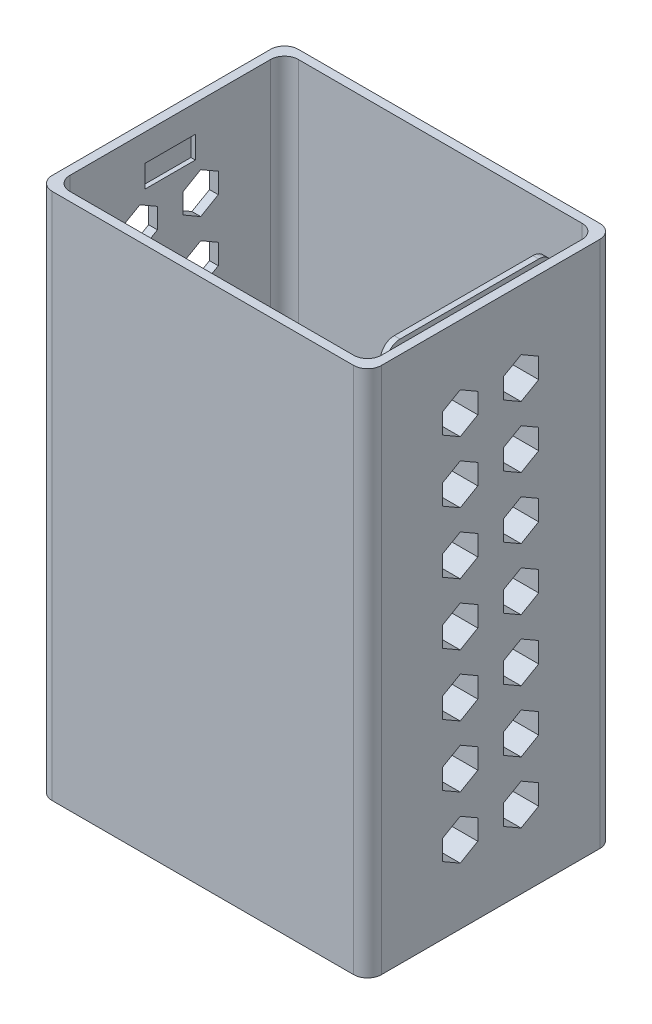
SolidWorks part; units mm, degrees
ref_plane "Front Plane" through (0, 0, 0) normal (0, 0, 1) x (1, 0, 0)
ref_plane "Top Plane" through (0, 0, 0) normal (0, 1, 0) x (1, 0, 0)
ref_plane "Right Plane" through (0, 0, 0) normal (1, 0, 0) x (0, 0, -1)
sketch "Sketch1" plane through (0, 0, 0) normal (0, 1, 0) x (1, 0, 0)
  line L0 (-6.35, 6.35) -> (-6.35, -171.3484)
  line L1 (0, 0) -> (224.9932, 0)
  line L2 (0, 0) -> (0, -164.9984)
  line L3 (0, -164.9984) -> (224.9932, -164.9984)
  line L4 (224.9932, 0) -> (224.9932, -164.9984)
  line L5 (-6.35, -171.3484) -> (231.3432, -171.3484)
  line L6 (231.3432, 6.35) -> (231.3432, -171.3484)
  line L7 (-6.35, 6.35) -> (231.3432, 6.35)
  dimension "D1" = 224.9932
  dimension "D2" = 164.9984
  dimension "D3" = 6.35
extrude "Boss-Extrude1" add sketch "Sketch1" along normal blind 374.65
sketch "Sketch4" plane through (224.9932, 0, 0) normal (-1, 0, 0) x (0, 0, 1)
  line L0 (164.9984, 0) -> (0, 0) construction
  line L1 (28.7274, 0) -> (136.1694, 0)
  line L2 (28.7274, 0) -> (28.7274, 374.65)
  line L3 (28.7274, 374.65) -> (136.1694, 374.65)
  line L4 (136.1694, 0) -> (136.1694, 374.65)
  line L5 (164.9984, 374.65) -> (0, 374.65) construction
  line L8 (164.9984, 374.65) -> (164.9984, 0) construction
  dimension "D1" = 107.442
  dimension "D2" = 28.829
extrude "Boss-Extrude2" add sketch "Sketch4" along normal blind 9.017
sketch "Sketch5" plane through (215.9762, 0, 0) normal (-1, 0, 0) x (0, 0, 1)
  line L0 (136.1694, 374.65) -> (28.7274, 374.65) construction
  line L5 (142.5194, 0) -> (22.3774, 0)
  line L6 (142.5194, 0) -> (142.5194, 374.65)
  line L7 (142.5194, 374.65) -> (22.3774, 374.65)
  line L8 (22.3774, 0) -> (22.3774, 374.65)
  line L9 (28.7274, 0) -> (136.1694, 0) construction
  line L11 (164.9984, 374.65) -> (164.9984, 0) construction
  line L12 (136.1694, 0) -> (136.1694, 374.65) construction
  line L13 (28.7274, 374.65) -> (28.7274, 0) construction
  dimension "D1" = 6.35
  dimension "D2" = 6.35
extrude "Boss-Extrude3" add sketch "Sketch5" along normal blind 4.191
sketch "Sketch7" plane through (0, 374.65, 0) normal (0, 1, 0) x (1, 0, 0)
  line L1 (215.9762, -136.1694) -> (224.9932, -136.1694)
  line L2 (215.9762, -136.1694) -> (215.9762, -28.7274)
  line L3 (215.9762, -28.7274) -> (224.9932, -28.7274)
  line L4 (224.9932, -136.1694) -> (224.9932, -28.7274)
extrude "Cut-Extrude1" cut sketch "Sketch7" against normal blind 21.59
sketch "Sketch10" plane through (0, 374.65, 0) normal (0, 1, 0) x (1, 0, 0)
  line L1 (211.7852, -142.5194) -> (215.9762, -142.5194)
  line L2 (211.7852, -142.5194) -> (211.7852, -22.3774)
  line L3 (211.7852, -22.3774) -> (215.9762, -22.3774)
  line L4 (215.9762, -142.5194) -> (215.9762, -22.3774)
extrude "Cut-Extrude2" cut sketch "Sketch10" against normal blind 5.588
fillet "Fillet1" radius 10 1 edges at (231.3432, 187.325, 171.3484)
fillet "Fillet2" radius 10 1 edges at (224.9932, 187.325, 164.9984)
fillet "Fillet3" radius 10 2 edges at (231.3432, 187.325, -6.35) (224.9932, 187.325, 0)
fillet "Fillet4" radius 10 2 edges at (-6.35, 187.325, 171.3484) (0, 187.325, 164.9984)
fillet "Fillet5" radius 10 2 edges at (0, 187.325, 0) (-6.35, 187.325, -6.35)
fillet "Fillet6" radius 10 2 edges at (220.4847, 353.06, 136.1694) (220.4847, 353.06, 28.7274)
fillet "Fillet7" radius 10 2 edges at (213.8807, 369.062, 22.3774) (213.8807, 369.062, 142.5194)
sketch "Sketch11" plane through (211.7852, 0, 0) normal (-1, 0, 0) x (0, 0, 1)
  line L0 (22.3774, 0) -> (142.5194, 0) construction
  line L1 (57.0484, 0) -> (107.8484, 0)
  line L2 (57.0484, 0) -> (57.0484, 15.24)
  line L3 (57.0484, 15.24) -> (107.8484, 15.24)
  line L4 (107.8484, 0) -> (107.8484, 15.24)
  line L5 (142.5194, 0) -> (142.5194, 359.062) construction
  dimension "D1" = 15.24
  dimension "D2" = 50.8
  dimension "D3" = 34.671
extrude "Boss-Extrude4" add sketch "Sketch11" along normal blind 19.9898
fillet "Fillet10" radius 10 2 edges at (191.7954, 7.62, 107.8484) (191.7954, 7.62, 57.0484)
fillet "Fillet11" radius 10 5 edges at (206.7903, 15.24, 107.8484) (194.7243, 15.24, 104.9195) (206.7903, 15.24, 57.0484) (194.7243, 15.24, 59.9773) (191.7954, 15.24, 82.4484)
sketch "Sketch12" plane through (0, 0, 0) normal (0, -1, 0) x (1, 0, 0)
  line L0 (231.3432, 161.3484) -> (231.3432, 3.65) construction
  line L1 (221.3432, -6.35) -> (3.65, -6.35) construction
  line L2 (-6.35, 3.65) -> (-6.35, 161.3484) construction
  line L3 (3.65, 171.3484) -> (221.3432, 171.3484) construction
  line L4 (231.3432, 161.3484) -> (231.3432, 3.65)
  line L5 (221.3432, -6.35) -> (3.65, -6.35)
  line L6 (-6.35, 3.65) -> (-6.35, 161.3484)
  line L7 (3.65, 171.3484) -> (221.3432, 171.3484)
  arc A0 (231.3432, 161.3484) -> (221.3432, 171.3484) centre (221.3432, 161.3484) ccw construction
  arc A1 (221.3432, -6.35) -> (231.3432, 3.65) centre (221.3432, 3.65) ccw construction
  arc A2 (-6.35, 3.65) -> (3.65, -6.35) centre (3.65, 3.65) ccw construction
  arc A3 (3.65, 171.3484) -> (-6.35, 161.3484) centre (3.65, 161.3484) ccw construction
  arc A4 (231.3432, 161.3484) -> (221.3432, 171.3484) centre (221.3432, 161.3484) ccw
  arc A5 (221.3432, -6.35) -> (231.3432, 3.65) centre (221.3432, 3.65) ccw
  arc A6 (-6.35, 3.65) -> (3.65, -6.35) centre (3.65, 3.65) ccw
  arc A7 (3.65, 171.3484) -> (-6.35, 161.3484) centre (3.65, 161.3484) ccw
extrude "Boss-Extrude5" add sketch "Sketch12" along normal blind 6.35
fillet "Fillet13" radius 10 9 edges at (224.9932, 0, 19.3637) (222.0643, 0, 2.9289) (112.4966, 0, 0) (2.9289, 0, 2.9289) (224.9932, 0, 145.5839) (222.0643, 0, 162.0695) (112.4966, 0, 164.9984) (2.9289, 0, 162.0695) (0, 0, 82.4992)
sketch "Sketch13" plane through (0, 0, 0) normal (1, 0, 0) x (0, 0, -1)
  line L0 (-10, 374.65) -> (-154.9984, 374.65) construction
  line L1 (-100.7542, 355.0412) -> (-64.356, 355.0412)
  line L2 (-100.7542, 355.0412) -> (-100.7542, 338.9122)
  line L3 (-100.7542, 338.9122) -> (-64.356, 338.9122)
  line L4 (-64.356, 355.0412) -> (-64.356, 338.9122)
  line L5 (-10, 10) -> (-10, 374.65) construction
  dimension "D1" = 19.6088
  dimension "D2" = 16.129
  dimension "D3" = 36.3982
  dimension "D4" = 54.356
extrude "Cut-Extrude4" cut sketch "Sketch13" against normal blind 3.175
sketch "Sketch15" plane through (0, -6.35, 0) normal (0, -1, 0) x (1, 0, 0)
  line L0 (177.8, 131.1399) -> (184.15, 134.8061)
  line L1 (196.85, 131.1399) -> (203.2, 134.8061)
  line L2 (203.2, 134.8061) -> (203.2, 142.1384)
  line L3 (203.2, 142.1384) -> (196.85, 145.8046)
  line L4 (196.85, 145.8046) -> (190.5, 142.1384)
  line L5 (190.5, 142.1384) -> (190.5, 134.8061)
  line L6 (190.5, 134.8061) -> (196.85, 131.1399)
  line L7 (171.45, 134.8061) -> (177.8, 131.1399)
  line L8 (171.45, 142.1384) -> (171.45, 134.8061)
  line L9 (177.8, 145.8046) -> (171.45, 142.1384)
  line L10 (184.15, 142.1384) -> (177.8, 145.8046)
  line L11 (184.15, 134.8061) -> (184.15, 142.1384)
  line L12 (158.75, 131.1399) -> (165.1, 134.8061)
  line L13 (152.4, 134.8061) -> (158.75, 131.1399)
  line L14 (152.4, 142.1384) -> (152.4, 134.8061)
  line L15 (158.75, 145.8046) -> (152.4, 142.1384)
  line L16 (165.1, 142.1384) -> (158.75, 145.8046)
  line L17 (165.1, 134.8061) -> (165.1, 142.1384)
  line L18 (139.7, 131.1399) -> (146.05, 134.8061)
  line L19 (133.35, 134.8061) -> (139.7, 131.1399)
  line L20 (133.35, 142.1384) -> (133.35, 134.8061)
  line L21 (139.7, 145.8046) -> (133.35, 142.1384)
  line L22 (146.05, 142.1384) -> (139.7, 145.8046)
  line L23 (146.05, 134.8061) -> (146.05, 142.1384)
  line L24 (120.65, 131.1399) -> (127, 134.8061)
  line L25 (114.3, 134.8061) -> (120.65, 131.1399)
  line L26 (114.3, 142.1384) -> (114.3, 134.8061)
  line L27 (120.65, 145.8046) -> (114.3, 142.1384)
  line L28 (127, 142.1384) -> (120.65, 145.8046)
  line L29 (127, 134.8061) -> (127, 142.1384)
  line L30 (-6.35, 161.3484) -> (-6.35, 3.65) construction
  line L31 (231.3432, 3.65) -> (231.3432, 161.3484) construction
  line L32 (3.65, -6.35) -> (221.3432, -6.35) construction
  line L38 (101.6, 131.1399) -> (107.95, 134.8061)
  line L39 (95.25, 134.8061) -> (101.6, 131.1399)
  line L40 (95.25, 142.1384) -> (95.25, 134.8061)
  line L41 (101.6, 145.8046) -> (95.25, 142.1384)
  line L42 (107.95, 142.1384) -> (101.6, 145.8046)
  line L43 (107.95, 134.8061) -> (107.95, 142.1384)
  line L44 (82.55, 131.1399) -> (88.9, 134.8061)
  line L45 (76.2, 134.8061) -> (82.55, 131.1399)
  line L46 (76.2, 142.1384) -> (76.2, 134.8061)
  line L47 (82.55, 145.8046) -> (76.2, 142.1384)
  line L48 (88.9, 142.1384) -> (82.55, 145.8046)
  line L49 (88.9, 134.8061) -> (88.9, 142.1384)
  line L50 (63.5, 131.1399) -> (69.85, 134.8061)
  line L51 (57.15, 134.8061) -> (63.5, 131.1399)
  line L52 (57.15, 142.1384) -> (57.15, 134.8061)
  line L53 (63.5, 145.8046) -> (57.15, 142.1384)
  line L54 (69.85, 142.1384) -> (63.5, 145.8046)
  line L55 (69.85, 134.8061) -> (69.85, 142.1384)
  line L56 (44.45, 131.1399) -> (50.8, 134.8061)
  line L57 (38.1, 134.8061) -> (44.45, 131.1399)
  line L58 (38.1, 142.1384) -> (38.1, 134.8061)
  line L59 (44.45, 145.8046) -> (38.1, 142.1384)
  line L60 (50.8, 142.1384) -> (44.45, 145.8046)
  line L61 (50.8, 134.8061) -> (50.8, 142.1384)
  line L62 (25.4, 131.1399) -> (31.75, 134.8061)
  line L63 (19.05, 134.8061) -> (25.4, 131.1399)
  line L64 (19.05, 142.1384) -> (19.05, 134.8061)
  line L65 (25.4, 145.8046) -> (19.05, 142.1384)
  line L66 (31.75, 142.1384) -> (25.4, 145.8046)
  line L67 (31.75, 134.8061) -> (31.75, 142.1384)
  line L74 (32.4716, 113.2256) -> (38.8216, 116.8918)
  line L75 (26.1216, 116.8918) -> (32.4716, 113.2256)
  line L76 (26.1216, 124.2241) -> (26.1216, 116.8918)
  line L77 (32.4716, 127.8903) -> (26.1216, 124.2241)
  line L78 (38.8216, 124.2241) -> (32.4716, 127.8903)
  line L79 (38.8216, 116.8918) -> (38.8216, 124.2241)
  line L80 (51.5216, 113.2256) -> (57.8716, 116.8918)
  line L81 (57.8716, 116.8918) -> (57.8716, 124.2241)
  line L82 (57.8716, 124.2241) -> (51.5216, 127.8903)
  line L83 (51.5216, 127.8903) -> (45.1716, 124.2241)
  line L84 (45.1716, 124.2241) -> (45.1716, 116.8918)
  line L85 (45.1716, 116.8918) -> (51.5216, 113.2256)
  line L86 (70.5716, 113.2256) -> (76.9216, 116.8918)
  line L87 (76.9216, 116.8918) -> (76.9216, 124.2241)
  line L88 (76.9216, 124.2241) -> (70.5716, 127.8903)
  line L89 (70.5716, 127.8903) -> (64.2216, 124.2241)
  line L90 (64.2216, 124.2241) -> (64.2216, 116.8918)
  line L91 (64.2216, 116.8918) -> (70.5716, 113.2256)
  line L92 (89.6216, 113.2256) -> (95.9716, 116.8918)
  line L93 (95.9716, 116.8918) -> (95.9716, 124.2241)
  line L94 (95.9716, 124.2241) -> (89.6216, 127.8903)
  line L95 (89.6216, 127.8903) -> (83.2716, 124.2241)
  line L96 (83.2716, 124.2241) -> (83.2716, 116.8918)
  line L97 (83.2716, 116.8918) -> (89.6216, 113.2256)
  line L98 (108.6716, 113.2256) -> (115.0216, 116.8918)
  line L99 (115.0216, 116.8918) -> (115.0216, 124.2241)
  line L100 (115.0216, 124.2241) -> (108.6716, 127.8903)
  line L101 (108.6716, 127.8903) -> (102.3216, 124.2241)
  line L102 (102.3216, 124.2241) -> (102.3216, 116.8918)
  line L103 (102.3216, 116.8918) -> (108.6716, 113.2256)
  line L104 (127.7216, 113.2256) -> (134.0716, 116.8918)
  line L105 (134.0716, 116.8918) -> (134.0716, 124.2241)
  line L106 (134.0716, 124.2241) -> (127.7216, 127.8903)
  line L107 (127.7216, 127.8903) -> (121.3716, 124.2241)
  line L108 (121.3716, 124.2241) -> (121.3716, 116.8918)
  line L109 (121.3716, 116.8918) -> (127.7216, 113.2256)
  line L110 (146.7716, 113.2256) -> (153.1216, 116.8918)
  line L111 (153.1216, 116.8918) -> (153.1216, 124.2241)
  line L112 (153.1216, 124.2241) -> (146.7716, 127.8903)
  line L113 (146.7716, 127.8903) -> (140.4216, 124.2241)
  line L114 (140.4216, 124.2241) -> (140.4216, 116.8918)
  line L115 (140.4216, 116.8918) -> (146.7716, 113.2256)
  line L116 (165.8216, 113.2256) -> (172.1716, 116.8918)
  line L117 (172.1716, 116.8918) -> (172.1716, 124.2241)
  line L118 (172.1716, 124.2241) -> (165.8216, 127.8903)
  line L119 (165.8216, 127.8903) -> (159.4716, 124.2241)
  line L120 (159.4716, 124.2241) -> (159.4716, 116.8918)
  line L121 (159.4716, 116.8918) -> (165.8216, 113.2256)
  line L122 (184.8716, 113.2256) -> (191.2216, 116.8918)
  line L123 (191.2216, 116.8918) -> (191.2216, 124.2241)
  line L124 (191.2216, 124.2241) -> (184.8716, 127.8903)
  line L125 (184.8716, 127.8903) -> (178.5216, 124.2241)
  line L126 (178.5216, 124.2241) -> (178.5216, 116.8918)
  line L127 (178.5216, 116.8918) -> (184.8716, 113.2256)
  line L128 (25.4, 95.3113) -> (31.75, 98.9775)
  line L129 (31.75, 98.9775) -> (31.75, 106.3099)
  line L130 (31.75, 106.3099) -> (25.4, 109.976)
  line L131 (25.4, 109.976) -> (19.05, 106.3099)
  line L132 (19.05, 106.3099) -> (19.05, 98.9775)
  line L133 (19.05, 98.9775) -> (25.4, 95.3113)
  line L134 (44.45, 95.3113) -> (50.8, 98.9775)
  line L135 (50.8, 98.9775) -> (50.8, 106.3099)
  line L136 (50.8, 106.3099) -> (44.45, 109.976)
  line L137 (44.45, 109.976) -> (38.1, 106.3099)
  line L138 (38.1, 106.3099) -> (38.1, 98.9775)
  line L139 (38.1, 98.9775) -> (44.45, 95.3113)
  line L140 (63.5, 95.3113) -> (69.85, 98.9775)
  line L141 (69.85, 98.9775) -> (69.85, 106.3099)
  line L142 (69.85, 106.3099) -> (63.5, 109.976)
  line L143 (63.5, 109.976) -> (57.15, 106.3099)
  line L144 (57.15, 106.3099) -> (57.15, 98.9775)
  line L145 (57.15, 98.9775) -> (63.5, 95.3113)
  line L146 (82.55, 95.3113) -> (88.9, 98.9775)
  line L147 (88.9, 98.9775) -> (88.9, 106.3099)
  line L148 (88.9, 106.3099) -> (82.55, 109.976)
  line L149 (82.55, 109.976) -> (76.2, 106.3099)
  line L150 (76.2, 106.3099) -> (76.2, 98.9775)
  line L151 (76.2, 98.9775) -> (82.55, 95.3113)
  line L152 (101.6, 95.3113) -> (107.95, 98.9775)
  line L153 (107.95, 98.9775) -> (107.95, 106.3099)
  line L154 (107.95, 106.3099) -> (101.6, 109.976)
  line L155 (101.6, 109.976) -> (95.25, 106.3099)
  line L156 (95.25, 106.3099) -> (95.25, 98.9775)
  line L157 (95.25, 98.9775) -> (101.6, 95.3113)
  line L158 (120.65, 95.3113) -> (127, 98.9775)
  line L159 (127, 98.9775) -> (127, 106.3099)
  line L160 (127, 106.3099) -> (120.65, 109.976)
  line L161 (120.65, 109.976) -> (114.3, 106.3099)
  line L162 (114.3, 106.3099) -> (114.3, 98.9775)
  line L163 (114.3, 98.9775) -> (120.65, 95.3113)
  line L164 (139.7, 95.3113) -> (146.05, 98.9775)
  line L165 (146.05, 98.9775) -> (146.05, 106.3099)
  line L166 (146.05, 106.3099) -> (139.7, 109.976)
  line L167 (139.7, 109.976) -> (133.35, 106.3099)
  line L168 (133.35, 106.3099) -> (133.35, 98.9775)
  line L169 (133.35, 98.9775) -> (139.7, 95.3113)
  line L170 (158.75, 95.3113) -> (165.1, 98.9775)
  line L171 (165.1, 98.9775) -> (165.1, 106.3099)
  line L172 (165.1, 106.3099) -> (158.75, 109.976)
  line L173 (158.75, 109.976) -> (152.4, 106.3099)
  line L174 (152.4, 106.3099) -> (152.4, 98.9775)
  line L175 (152.4, 98.9775) -> (158.75, 95.3113)
  line L176 (177.8, 95.3113) -> (184.15, 98.9775)
  line L177 (184.15, 98.9775) -> (184.15, 106.3099)
  line L178 (184.15, 106.3099) -> (177.8, 109.976)
  line L179 (177.8, 109.976) -> (171.45, 106.3099)
  line L180 (171.45, 106.3099) -> (171.45, 98.9775)
  line L181 (171.45, 98.9775) -> (177.8, 95.3113)
  line L188 (184.8716, 77.3971) -> (191.2216, 81.0632)
  line L189 (191.2216, 81.0632) -> (191.2216, 88.3956)
  line L190 (191.2216, 88.3956) -> (184.8716, 92.0618)
  line L191 (184.8716, 92.0618) -> (178.5216, 88.3956)
  line L192 (178.5216, 88.3956) -> (178.5216, 81.0632)
  line L193 (178.5216, 81.0632) -> (184.8716, 77.3971)
  line L194 (165.8216, 77.3971) -> (172.1716, 81.0632)
  line L195 (172.1716, 81.0632) -> (172.1716, 88.3956)
  line L196 (172.1716, 88.3956) -> (165.8216, 92.0618)
  line L197 (165.8216, 92.0618) -> (159.4716, 88.3956)
  line L198 (159.4716, 88.3956) -> (159.4716, 81.0632)
  line L199 (159.4716, 81.0632) -> (165.8216, 77.3971)
  line L200 (146.7716, 77.3971) -> (153.1216, 81.0632)
  line L201 (153.1216, 81.0632) -> (153.1216, 88.3956)
  line L202 (153.1216, 88.3956) -> (146.7716, 92.0618)
  line L203 (146.7716, 92.0618) -> (140.4216, 88.3956)
  line L204 (140.4216, 88.3956) -> (140.4216, 81.0632)
  line L205 (140.4216, 81.0632) -> (146.7716, 77.3971)
  line L206 (127.7216, 77.3971) -> (134.0716, 81.0632)
  line L207 (134.0716, 81.0632) -> (134.0716, 88.3956)
  line L208 (134.0716, 88.3956) -> (127.7216, 92.0618)
  line L209 (127.7216, 92.0618) -> (121.3716, 88.3956)
  line L210 (121.3716, 88.3956) -> (121.3716, 81.0632)
  line L211 (121.3716, 81.0632) -> (127.7216, 77.3971)
  line L212 (108.6716, 77.3971) -> (115.0216, 81.0632)
  line L213 (115.0216, 81.0632) -> (115.0216, 88.3956)
  line L214 (115.0216, 88.3956) -> (108.6716, 92.0618)
  line L215 (108.6716, 92.0618) -> (102.3216, 88.3956)
  line L216 (102.3216, 88.3956) -> (102.3216, 81.0632)
  line L217 (102.3216, 81.0632) -> (108.6716, 77.3971)
  line L218 (89.6216, 77.3971) -> (95.9716, 81.0632)
  line L219 (95.9716, 81.0632) -> (95.9716, 88.3956)
  line L220 (95.9716, 88.3956) -> (89.6216, 92.0618)
  line L221 (89.6216, 92.0618) -> (83.2716, 88.3956)
  line L222 (83.2716, 88.3956) -> (83.2716, 81.0632)
  line L223 (83.2716, 81.0632) -> (89.6216, 77.3971)
  line L224 (70.5716, 77.3971) -> (76.9216, 81.0632)
  line L225 (76.9216, 81.0632) -> (76.9216, 88.3956)
  line L226 (76.9216, 88.3956) -> (70.5716, 92.0618)
  line L227 (70.5716, 92.0618) -> (64.2216, 88.3956)
  line L228 (64.2216, 88.3956) -> (64.2216, 81.0632)
  line L229 (64.2216, 81.0632) -> (70.5716, 77.3971)
  line L230 (51.5216, 77.3971) -> (57.8716, 81.0632)
  line L231 (57.8716, 81.0632) -> (57.8716, 88.3956)
  line L232 (57.8716, 88.3956) -> (51.5216, 92.0618)
  line L233 (51.5216, 92.0618) -> (45.1716, 88.3956)
  line L234 (45.1716, 88.3956) -> (45.1716, 81.0632)
  line L235 (45.1716, 81.0632) -> (51.5216, 77.3971)
  line L236 (32.4716, 77.3971) -> (38.8216, 81.0632)
  line L237 (38.8216, 81.0632) -> (38.8216, 88.3956)
  line L238 (38.8216, 88.3956) -> (32.4716, 92.0618)
  line L239 (32.4716, 92.0618) -> (26.1216, 88.3956)
  line L240 (26.1216, 88.3956) -> (26.1216, 81.0632)
  line L241 (26.1216, 81.0632) -> (32.4716, 77.3971)
  line L242 (25.4, 59.4828) -> (31.75, 63.149)
  line L243 (31.75, 63.149) -> (31.75, 70.4813)
  line L244 (31.75, 70.4813) -> (25.4, 74.1475)
  line L245 (25.4, 74.1475) -> (19.05, 70.4813)
  line L246 (19.05, 70.4813) -> (19.05, 63.149)
  line L247 (19.05, 63.149) -> (25.4, 59.4828)
  line L248 (44.45, 59.4828) -> (50.8, 63.149)
  line L249 (50.8, 63.149) -> (50.8, 70.4813)
  line L250 (50.8, 70.4813) -> (44.45, 74.1475)
  line L251 (44.45, 74.1475) -> (38.1, 70.4813)
  line L252 (38.1, 70.4813) -> (38.1, 63.149)
  line L253 (38.1, 63.149) -> (44.45, 59.4828)
  line L254 (63.5, 59.4828) -> (69.85, 63.149)
  line L255 (69.85, 63.149) -> (69.85, 70.4813)
  line L256 (69.85, 70.4813) -> (63.5, 74.1475)
  line L257 (63.5, 74.1475) -> (57.15, 70.4813)
  line L258 (57.15, 70.4813) -> (57.15, 63.149)
  line L259 (57.15, 63.149) -> (63.5, 59.4828)
  line L260 (82.55, 59.4828) -> (88.9, 63.149)
  line L261 (88.9, 63.149) -> (88.9, 70.4813)
  line L262 (88.9, 70.4813) -> (82.55, 74.1475)
  line L263 (82.55, 74.1475) -> (76.2, 70.4813)
  line L264 (76.2, 70.4813) -> (76.2, 63.149)
  line L265 (76.2, 63.149) -> (82.55, 59.4828)
  line L266 (101.6, 59.4828) -> (107.95, 63.149)
  line L267 (107.95, 63.149) -> (107.95, 70.4813)
  line L268 (107.95, 70.4813) -> (101.6, 74.1475)
  line L269 (101.6, 74.1475) -> (95.25, 70.4813)
  line L270 (95.25, 70.4813) -> (95.25, 63.149)
  line L271 (95.25, 63.149) -> (101.6, 59.4828)
  line L272 (120.65, 59.4828) -> (127, 63.149)
  line L273 (127, 63.149) -> (127, 70.4813)
  line L274 (127, 70.4813) -> (120.65, 74.1475)
  line L275 (120.65, 74.1475) -> (114.3, 70.4813)
  line L276 (114.3, 70.4813) -> (114.3, 63.149)
  line L277 (114.3, 63.149) -> (120.65, 59.4828)
  line L278 (139.7, 59.4828) -> (146.05, 63.149)
  line L279 (146.05, 63.149) -> (146.05, 70.4813)
  line L280 (146.05, 70.4813) -> (139.7, 74.1475)
  line L281 (139.7, 74.1475) -> (133.35, 70.4813)
  line L282 (133.35, 70.4813) -> (133.35, 63.149)
  line L283 (133.35, 63.149) -> (139.7, 59.4828)
  line L284 (158.75, 59.4828) -> (165.1, 63.149)
  line L285 (165.1, 63.149) -> (165.1, 70.4813)
  line L286 (165.1, 70.4813) -> (158.75, 74.1475)
  line L287 (158.75, 74.1475) -> (152.4, 70.4813)
  line L288 (152.4, 70.4813) -> (152.4, 63.149)
  line L289 (152.4, 63.149) -> (158.75, 59.4828)
  line L290 (177.8, 59.4828) -> (184.15, 63.149)
  line L291 (184.15, 63.149) -> (184.15, 70.4813)
  line L292 (184.15, 70.4813) -> (177.8, 74.1475)
  line L293 (177.8, 74.1475) -> (171.45, 70.4813)
  line L294 (171.45, 70.4813) -> (171.45, 63.149)
  line L295 (171.45, 63.149) -> (177.8, 59.4828)
  line L302 (184.8716, 41.5685) -> (191.2216, 45.2347)
  line L303 (191.2216, 45.2347) -> (191.2216, 52.567)
  line L304 (191.2216, 52.567) -> (184.8716, 56.2332)
  line L305 (184.8716, 56.2332) -> (178.5216, 52.567)
  line L306 (178.5216, 52.567) -> (178.5216, 45.2347)
  line L307 (178.5216, 45.2347) -> (184.8716, 41.5685)
  line L308 (165.8216, 41.5685) -> (172.1716, 45.2347)
  line L309 (172.1716, 45.2347) -> (172.1716, 52.567)
  line L310 (172.1716, 52.567) -> (165.8216, 56.2332)
  line L311 (165.8216, 56.2332) -> (159.4716, 52.567)
  line L312 (159.4716, 52.567) -> (159.4716, 45.2347)
  line L313 (159.4716, 45.2347) -> (165.8216, 41.5685)
  line L314 (146.7716, 41.5685) -> (153.1216, 45.2347)
  line L315 (153.1216, 45.2347) -> (153.1216, 52.567)
  line L316 (153.1216, 52.567) -> (146.7716, 56.2332)
  line L317 (146.7716, 56.2332) -> (140.4216, 52.567)
  line L318 (140.4216, 52.567) -> (140.4216, 45.2347)
  line L319 (140.4216, 45.2347) -> (146.7716, 41.5685)
  line L320 (127.7216, 41.5685) -> (134.0716, 45.2347)
  line L321 (134.0716, 45.2347) -> (134.0716, 52.567)
  line L322 (134.0716, 52.567) -> (127.7216, 56.2332)
  line L323 (127.7216, 56.2332) -> (121.3716, 52.567)
  line L324 (121.3716, 52.567) -> (121.3716, 45.2347)
  line L325 (121.3716, 45.2347) -> (127.7216, 41.5685)
  line L326 (108.6716, 41.5685) -> (115.0216, 45.2347)
  line L327 (115.0216, 45.2347) -> (115.0216, 52.567)
  line L328 (115.0216, 52.567) -> (108.6716, 56.2332)
  line L329 (108.6716, 56.2332) -> (102.3216, 52.567)
  line L330 (102.3216, 52.567) -> (102.3216, 45.2347)
  line L331 (102.3216, 45.2347) -> (108.6716, 41.5685)
  line L332 (89.6216, 41.5685) -> (95.9716, 45.2347)
  line L333 (95.9716, 45.2347) -> (95.9716, 52.567)
  line L334 (95.9716, 52.567) -> (89.6216, 56.2332)
  line L335 (89.6216, 56.2332) -> (83.2716, 52.567)
  line L336 (83.2716, 52.567) -> (83.2716, 45.2347)
  line L337 (83.2716, 45.2347) -> (89.6216, 41.5685)
  line L338 (70.5716, 41.5685) -> (76.9216, 45.2347)
  line L339 (76.9216, 45.2347) -> (76.9216, 52.567)
  line L340 (76.9216, 52.567) -> (70.5716, 56.2332)
  line L341 (70.5716, 56.2332) -> (64.2216, 52.567)
  line L342 (64.2216, 52.567) -> (64.2216, 45.2347)
  line L343 (64.2216, 45.2347) -> (70.5716, 41.5685)
  line L344 (51.5216, 41.5685) -> (57.8716, 45.2347)
  line L345 (57.8716, 45.2347) -> (57.8716, 52.567)
  line L346 (57.8716, 52.567) -> (51.5216, 56.2332)
  line L347 (51.5216, 56.2332) -> (45.1716, 52.567)
  line L348 (45.1716, 52.567) -> (45.1716, 45.2347)
  line L349 (45.1716, 45.2347) -> (51.5216, 41.5685)
  line L350 (32.4716, 41.5685) -> (38.8216, 45.2347)
  line L351 (38.8216, 45.2347) -> (38.8216, 52.567)
  line L352 (38.8216, 52.567) -> (32.4716, 56.2332)
  line L353 (32.4716, 56.2332) -> (26.1216, 52.567)
  line L354 (26.1216, 52.567) -> (26.1216, 45.2347)
  line L355 (26.1216, 45.2347) -> (32.4716, 41.5685)
  line L356 (25.4, 23.6542) -> (31.75, 27.3204)
  line L357 (31.75, 27.3204) -> (31.75, 34.6528)
  line L358 (31.75, 34.6528) -> (25.4, 38.3189)
  line L359 (25.4, 38.3189) -> (19.05, 34.6528)
  line L360 (19.05, 34.6528) -> (19.05, 27.3204)
  line L361 (19.05, 27.3204) -> (25.4, 23.6542)
  line L362 (44.45, 23.6542) -> (50.8, 27.3204)
  line L363 (50.8, 27.3204) -> (50.8, 34.6528)
  line L364 (50.8, 34.6528) -> (44.45, 38.3189)
  line L365 (44.45, 38.3189) -> (38.1, 34.6528)
  line L366 (38.1, 34.6528) -> (38.1, 27.3204)
  line L367 (38.1, 27.3204) -> (44.45, 23.6542)
  line L368 (63.5, 23.6542) -> (69.85, 27.3204)
  line L369 (69.85, 27.3204) -> (69.85, 34.6528)
  line L370 (69.85, 34.6528) -> (63.5, 38.3189)
  line L371 (63.5, 38.3189) -> (57.15, 34.6528)
  line L372 (57.15, 34.6528) -> (57.15, 27.3204)
  line L373 (57.15, 27.3204) -> (63.5, 23.6542)
  line L374 (82.55, 23.6542) -> (88.9, 27.3204)
  line L375 (88.9, 27.3204) -> (88.9, 34.6528)
  line L376 (88.9, 34.6528) -> (82.55, 38.3189)
  line L377 (82.55, 38.3189) -> (76.2, 34.6528)
  line L378 (76.2, 34.6528) -> (76.2, 27.3204)
  line L379 (76.2, 27.3204) -> (82.55, 23.6542)
  line L380 (101.6, 23.6542) -> (107.95, 27.3204)
  line L381 (107.95, 27.3204) -> (107.95, 34.6528)
  line L382 (107.95, 34.6528) -> (101.6, 38.3189)
  line L383 (101.6, 38.3189) -> (95.25, 34.6528)
  line L384 (95.25, 34.6528) -> (95.25, 27.3204)
  line L385 (95.25, 27.3204) -> (101.6, 23.6542)
  line L386 (120.65, 23.6542) -> (127, 27.3204)
  line L387 (127, 27.3204) -> (127, 34.6528)
  line L388 (127, 34.6528) -> (120.65, 38.3189)
  line L389 (120.65, 38.3189) -> (114.3, 34.6528)
  line L390 (114.3, 34.6528) -> (114.3, 27.3204)
  line L391 (114.3, 27.3204) -> (120.65, 23.6542)
  line L392 (139.7, 23.6542) -> (146.05, 27.3204)
  line L393 (146.05, 27.3204) -> (146.05, 34.6528)
  line L394 (146.05, 34.6528) -> (139.7, 38.3189)
  line L395 (139.7, 38.3189) -> (133.35, 34.6528)
  line L396 (133.35, 34.6528) -> (133.35, 27.3204)
  line L397 (133.35, 27.3204) -> (139.7, 23.6542)
  line L398 (158.75, 23.6542) -> (165.1, 27.3204)
  line L399 (165.1, 27.3204) -> (165.1, 34.6528)
  line L400 (165.1, 34.6528) -> (158.75, 38.3189)
  line L401 (158.75, 38.3189) -> (152.4, 34.6528)
  line L402 (152.4, 34.6528) -> (152.4, 27.3204)
  line L403 (152.4, 27.3204) -> (158.75, 23.6542)
  line L404 (177.8, 23.6542) -> (184.15, 27.3204)
  line L405 (184.15, 27.3204) -> (184.15, 34.6528)
  line L406 (184.15, 34.6528) -> (177.8, 38.3189)
  line L407 (177.8, 38.3189) -> (171.45, 34.6528)
  line L408 (171.45, 34.6528) -> (171.45, 27.3204)
  line L409 (171.45, 27.3204) -> (177.8, 23.6542)
  line L410 (196.85, 23.6542) -> (203.2, 27.3204)
  line L411 (203.2, 27.3204) -> (203.2, 34.6528)
  line L412 (203.2, 34.6528) -> (196.85, 38.3189)
  line L413 (196.85, 38.3189) -> (190.5, 34.6528)
  line L414 (190.5, 34.6528) -> (190.5, 27.3204)
  line L415 (190.5, 27.3204) -> (196.85, 23.6542)
  line L416 (190.5, 106.3099) -> (190.5, 98.9775) [skipped]
  line L417 (190.5, 98.9775) -> (196.85, 95.3113) [skipped]
  line L418 (196.85, 95.3113) -> (203.2, 98.9775) [skipped]
  line L419 (203.2, 98.9775) -> (203.2, 106.3099) [skipped]
  line L420 (203.2, 106.3099) -> (196.85, 109.976) [skipped]
  line L421 (196.85, 109.976) -> (190.5, 106.3099) [skipped]
  line L422 (203.2, 63.149) -> (203.2, 70.4813) [skipped]
  line L423 (196.85, 59.4828) -> (203.2, 63.149) [skipped]
  line L424 (190.5, 63.149) -> (196.85, 59.4828) [skipped]
  line L425 (190.5, 70.4813) -> (190.5, 63.149) [skipped]
  line L426 (196.85, 74.1475) -> (190.5, 70.4813) [skipped]
  line L427 (203.2, 70.4813) -> (196.85, 74.1475) [skipped]
  circle A0 centre (196.85, 138.4722) radius 6.35 construction
  dimension "D2" = 25.4
  dimension "D4" = 6.35
  dimension "D5" = 6.35
  dimension "D7" = 28.1432
  dimension "D8" = 7.3323
  dimension "D10" = 6.35
  dimension "D12" = 6.35
  dimension "D13" = 30.0042
  dimension "D14" = 40.1216
  dimension "D15" = 32.4716
  dimension "D16" = 6.35
  dimension "D17" = 9.525
  dimension "D18" = 9.525
  dimension "D3" = 10
  dimension "D6" = 9
  dimension "D9" = 3
  dimension "D11" = 2
sketch "Sketch17" plane through (0, -6.35, 0) normal (0, -1, 0) x (1, 0, 0)
extrude "Cut-Extrude5" cut sketch "Sketch15" against normal blind 6.35
sketch "Sketch18" plane through (211.7852, 0, 0) normal (-1, 0, 0) x (0, 0, 1)
  line L0 (73.1774, 323.6297) -> (60.4774, 330.962)
  line L1 (117.1194, 323.6297) -> (104.4194, 330.962)
  line L2 (104.4194, 330.962) -> (91.7194, 323.6297)
  line L3 (91.7194, 323.6297) -> (91.7194, 308.965)
  line L4 (91.7194, 308.965) -> (104.4194, 301.6326)
  line L5 (104.4194, 301.6326) -> (117.1194, 308.965)
  line L6 (117.1194, 308.965) -> (117.1194, 323.6297)
  line L7 (142.5194, 0) -> (142.5194, 359.062) construction
  line L8 (32.3774, 369.062) -> (132.5194, 369.062) construction
  line L9 (60.4774, 330.962) -> (47.7774, 323.6297)
  line L10 (47.7774, 323.6297) -> (47.7774, 308.965)
  line L11 (47.7774, 308.965) -> (60.4774, 301.6326)
  line L12 (60.4774, 301.6326) -> (73.1774, 308.965)
  line L13 (73.1774, 308.965) -> (73.1774, 323.6297)
  line L14 (73.1774, 279.1797) -> (60.4774, 286.512)
  line L15 (60.4774, 286.512) -> (47.7774, 279.1797)
  line L16 (47.7774, 279.1797) -> (47.7774, 264.515)
  line L17 (47.7774, 264.515) -> (60.4774, 257.1826)
  line L18 (60.4774, 257.1826) -> (73.1774, 264.515)
  line L19 (73.1774, 264.515) -> (73.1774, 279.1797)
  line L20 (73.1774, 234.7297) -> (60.4774, 242.062)
  line L21 (60.4774, 242.062) -> (47.7774, 234.7297)
  line L22 (47.7774, 234.7297) -> (47.7774, 220.065)
  line L23 (47.7774, 220.065) -> (60.4774, 212.7326)
  line L24 (60.4774, 212.7326) -> (73.1774, 220.065)
  line L25 (73.1774, 220.065) -> (73.1774, 234.7297)
  line L26 (73.1774, 190.2797) -> (60.4774, 197.612)
  line L27 (60.4774, 197.612) -> (47.7774, 190.2797)
  line L28 (47.7774, 190.2797) -> (47.7774, 175.615)
  line L29 (47.7774, 175.615) -> (60.4774, 168.2826)
  line L30 (60.4774, 168.2826) -> (73.1774, 175.615)
  line L31 (73.1774, 175.615) -> (73.1774, 190.2797)
  line L32 (73.1774, 145.8297) -> (60.4774, 153.162)
  line L33 (60.4774, 153.162) -> (47.7774, 145.8297)
  line L34 (47.7774, 145.8297) -> (47.7774, 131.165)
  line L35 (47.7774, 131.165) -> (60.4774, 123.8326)
  line L36 (60.4774, 123.8326) -> (73.1774, 131.165)
  line L37 (73.1774, 131.165) -> (73.1774, 145.8297)
  line L38 (73.1774, 101.3797) -> (60.4774, 108.712)
  line L39 (60.4774, 108.712) -> (47.7774, 101.3797)
  line L40 (47.7774, 101.3797) -> (47.7774, 86.715)
  line L41 (47.7774, 86.715) -> (60.4774, 79.3826)
  line L42 (60.4774, 79.3826) -> (73.1774, 86.715)
  line L43 (73.1774, 86.715) -> (73.1774, 101.3797)
  line L44 (73.1774, 56.9297) -> (60.4774, 64.262)
  line L45 (60.4774, 64.262) -> (47.7774, 56.9297)
  line L46 (47.7774, 56.9297) -> (47.7774, 42.265)
  line L47 (47.7774, 42.265) -> (60.4774, 34.9326)
  line L48 (60.4774, 34.9326) -> (73.1774, 42.265)
  line L49 (73.1774, 42.265) -> (73.1774, 56.9297)
  line L56 (117.1194, 279.1797) -> (104.4194, 286.512)
  line L57 (104.4194, 286.512) -> (91.7194, 279.1797)
  line L58 (91.7194, 279.1797) -> (91.7194, 264.515)
  line L59 (91.7194, 264.515) -> (104.4194, 257.1826)
  line L60 (104.4194, 257.1826) -> (117.1194, 264.515)
  line L61 (117.1194, 264.515) -> (117.1194, 279.1797)
  line L62 (117.1194, 234.7297) -> (104.4194, 242.062)
  line L63 (104.4194, 242.062) -> (91.7194, 234.7297)
  line L64 (91.7194, 234.7297) -> (91.7194, 220.065)
  line L65 (91.7194, 220.065) -> (104.4194, 212.7326)
  line L66 (104.4194, 212.7326) -> (117.1194, 220.065)
  line L67 (117.1194, 220.065) -> (117.1194, 234.7297)
  line L68 (117.1194, 190.2797) -> (104.4194, 197.612)
  line L69 (104.4194, 197.612) -> (91.7194, 190.2797)
  line L70 (91.7194, 190.2797) -> (91.7194, 175.615)
  line L71 (91.7194, 175.615) -> (104.4194, 168.2826)
  line L72 (104.4194, 168.2826) -> (117.1194, 175.615)
  line L73 (117.1194, 175.615) -> (117.1194, 190.2797)
  line L74 (117.1194, 145.8297) -> (104.4194, 153.162)
  line L75 (104.4194, 153.162) -> (91.7194, 145.8297)
  line L76 (91.7194, 145.8297) -> (91.7194, 131.165)
  line L77 (91.7194, 131.165) -> (104.4194, 123.8326)
  line L78 (104.4194, 123.8326) -> (117.1194, 131.165)
  line L79 (117.1194, 131.165) -> (117.1194, 145.8297)
  line L80 (117.1194, 101.3797) -> (104.4194, 108.712)
  line L81 (104.4194, 108.712) -> (91.7194, 101.3797)
  line L82 (91.7194, 101.3797) -> (91.7194, 86.715)
  line L83 (91.7194, 86.715) -> (104.4194, 79.3826)
  line L84 (104.4194, 79.3826) -> (117.1194, 86.715)
  line L85 (117.1194, 86.715) -> (117.1194, 101.3797)
  line L86 (117.1194, 56.9297) -> (104.4194, 64.262)
  line L87 (104.4194, 64.262) -> (91.7194, 56.9297)
  line L88 (91.7194, 56.9297) -> (91.7194, 42.265)
  line L89 (91.7194, 42.265) -> (104.4194, 34.9326)
  line L90 (104.4194, 34.9326) -> (117.1194, 42.265)
  line L91 (117.1194, 42.265) -> (117.1194, 56.9297)
  line L98 (22.3774, 359.062) -> (22.3774, 0) construction
  line L99 (91.7194, 12.4797) -> (91.7194, -2.185) [skipped]
  line L100 (91.7194, -2.185) -> (104.4194, -9.5174) [skipped]
  line L101 (104.4194, -9.5174) -> (117.1194, -2.185) [skipped]
  line L102 (117.1194, 12.4797) -> (104.4194, 19.812) [skipped]
  line L103 (117.1194, -2.185) -> (117.1194, 12.4797) [skipped]
  line L104 (104.4194, 19.812) -> (91.7194, 12.4797) [skipped]
  line L105 (73.1774, -2.185) -> (73.1774, 12.4797) [skipped]
  line L106 (60.4774, -9.5174) -> (73.1774, -2.185) [skipped]
  line L107 (47.7774, -2.185) -> (60.4774, -9.5174) [skipped]
  line L108 (47.7774, 12.4797) -> (47.7774, -2.185) [skipped]
  line L109 (60.4774, 19.812) -> (47.7774, 12.4797) [skipped]
  line L110 (73.1774, 12.4797) -> (60.4774, 19.812) [skipped]
  circle A0 centre (104.4194, 316.2973) radius 12.7 construction
  dimension "D2" = 25.4
  dimension "D1" = 25.4
  dimension "D3" = 38.1
  dimension "D6" = 25.4
  dimension "D4" = 2
  dimension "D5" = 8
extrude "Cut-Extrude6" cut sketch "Sketch18" against normal through all and the other way through all
